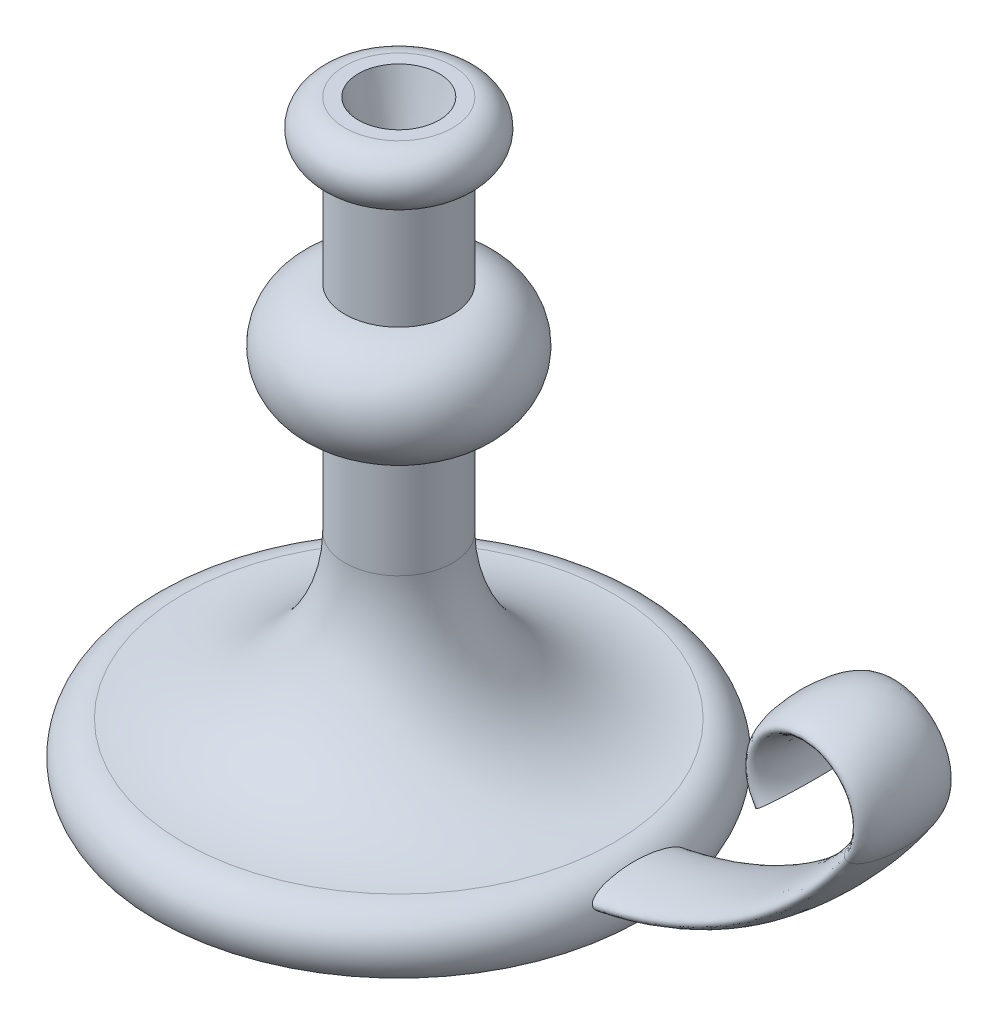
SolidWorks part; units mm, degrees
ref_plane "Front" through (0, 0, 0) normal (0, 0, 1) x (1, 0, 0)
ref_plane "Top" through (0, 0, 0) normal (0, 1, 0) x (1, 0, 0)
ref_plane "Right" through (0, 0, 0) normal (1, 0, 0) x (0, 0, -1)
sketch "Sketch1" plane through (0, 0, 0) normal (0, 0, 1) x (1, 0, 0)
  line L0 (0, 0) -> (0, -220)
  line L1 (0, -220) -> (90, -220)
  line L2 (0, 0) -> (20, 0)
  line L3 (20, -20) -> (20, -60)
  line L4 (20, -100) -> (20, -140)
  arc A0 (20, 0) -> (20, -20) centre (20, -10) cw
  arc A1 (20, -60) -> (20, -100) centre (20, -80) cw
  arc A2 (20, -140) -> (80, -200) centre (80, -140) ccw
  arc A4 (80, -200) -> (90, -220) centre (80, -212.5) cw
  dimension "D4" = 10
  dimension "D6" = 20
  dimension "D7" = 40
  dimension "D5" = 60
  dimension "D8" = 12.5
  dimension "D1" = 220
  dimension "D2" = 90
  dimension "D3" = 20
revolve "Revolve1" add sketch "Sketch1" angle 360 about L0
sketch "Sketch2" plane through (0, 0, 0) normal (0, 0, 1) x (1, 0, 0)
  line L0 (0, -210) -> (60, -210)
  line L1 (0, -264.9786) -> (0, -107.5429) construction
  line L2 (-90, -220) -> (90, -220) construction
  arc A0 (60, -210) -> (183.5921, -145) centre (60, -60) ccw
  arc A1 (183.5921, -145) -> (150.6342, -145) centre (167.1131, -133.6667) ccw
  point P10 (0, 0)
  dimension "D3" = 150
  dimension "D4" = 20
  dimension "D1" = 10
  dimension "D2" = 60
  dimension "D5" = 65
sketch "Sketch3" plane through (0, 0, 0) normal (1, 0, 0) x (0, 0, -1)
  ellipse E0 centre (0, -210) end of major axis (-17.5, -210) minor radius 5
  point P1 (0, 0)
  point P7 (0, 0)
  dimension "D1" = 35
  dimension "D2" = 10
sweep "Sweep1" add profiles "Sketch3" path "Sketch2"
sketch "Sketch4" plane through (0, 0, 0) normal (0, 1, 0) x (1, 0, 0)
  circle A0 centre (0, 0) radius 15
  dimension "D1" = 30
extrude "Cut-Extrude1" cut sketch "Sketch4" against normal blind 25 draft 15
